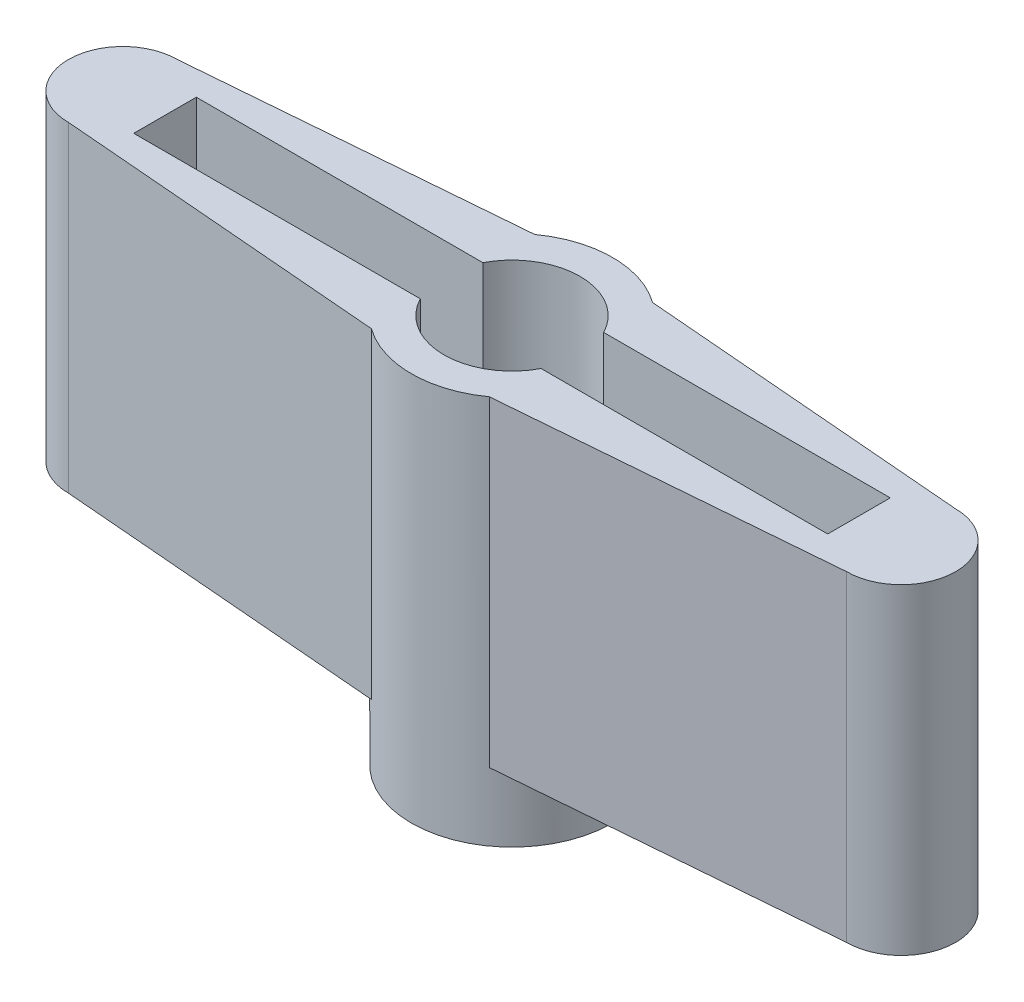
SolidWorks part; units mm, degrees
ref_plane "Alzado" through (0, 0, 0) normal (0, 0, 1) x (1, 0, 0)
ref_plane "Planta" through (0, 0, 0) normal (0, 1, 0) x (1, 0, 0)
ref_plane "Vista lateral" through (0, 0, 0) normal (1, 0, 0) x (0, 0, -1)
sketch "Croquis1" plane through (0, 0, 0) normal (0, 1, 0) x (1, 0, 0)
  circle A0 centre (0, 0) radius 3.7
  dimension "D1" = 7.4
extrude "Saliente-Extruir2" add sketch "Croquis1" along normal blind 4.3 contours A0
sketch "Croquis2" plane through (0, 0, 0) normal (0, -1, 0) x (1, 0, 0)
  circle A0 centre (0, 0) radius 2.5
  dimension "D1" = 5
extrude "Cortar-Extruir1" cut sketch "Croquis2" against normal blind 1.5
sketch "Croquis3" plane through (0, 4.3, 0) normal (0, 1, 0) x (1, 0, 0)
  circle A0 centre (0, 0) radius 2.5
  dimension "D1" = 5
extrude "Cortar-Extruir2" cut sketch "Croquis3" against normal blind 1
sketch "Croquis4" plane through (0, 3.3, 0) normal (0, 1, 0) x (1, 0, 0)
  circle A0 centre (0, 0) radius 1
  dimension "D1" = 2
extrude "Cortar-Extruir3" cut sketch "Croquis4" against normal blind 1.8
sketch "Croquis5" plane through (0, 4.3, 0) normal (0, 1, 0) x (1, 0, 0)
  line L0 (0, 0) -> (-2.1656, 0) construction
  line L1 (-2.1656, 3) -> (-3.1202, 0)
  line L2 (-3.1202, 0) -> (-2.1656, -3)
  line L3 (-2.1656, 0) -> (-2.5, 0) construction
  line L4 (-3.7, 0) -> (-16.3, 0) construction
  line L5 (-14.3, 0) -> (-14.3, 2) construction
  line L6 (-14.3, 0) -> (-14.3, -2) construction
  line L7 (-2.1656, 3) -> (-14.3, 2)
  line L8 (-2.1656, -3) -> (-14.3, -2)
  line L9 (0, 5.1944) -> (0, -4.3435) construction
  line L10 (3.1202, 0) -> (2.1656, -3)
  line L11 (2.1656, -3) -> (14.3, -2)
  line L12 (2.1656, 3) -> (14.3, 2)
  line L13 (2.1656, 3) -> (3.1202, 0)
  arc A0 (-14.3, 2) -> (-14.3, -2) centre (-14.3, 0) ccw
  arc A1 (14.3, 2) -> (14.3, -2) centre (14.3, 0) cw
  circle A3 centre (0, 0) radius 3.7 construction
  circle A4 centre (0, 0) radius 2.5 construction
  point P2 (-14.3, 0)
  dimension "D1" = 2.1656
  dimension "D2" = 12.6
  dimension "D3" = 2
  dimension "D4" = 2
  dimension "D5" = 2
extrude "Saliente-Extruir3" add sketch "Croquis5" against normal blind 1.8
sketch "Croquis6" plane through (0, 4.3, 0) normal (0, 1, 0) x (1, 0, 0)
  line L0 (0, 0) -> (-16.3, 0) construction
  line L1 (2, 0) -> (-14.3, 0) construction
  line L2 (4, 0) -> (-12.3, 0) construction
  line L3 (6, 0) -> (-10.3, 0) construction
  line L4 (8, 0) -> (-8.3, 0) construction
  line L5 (10, 0) -> (-6.3, 0) construction
  line L6 (0, 5.4913) -> (0, -4.5375) construction
  arc A0 (-14.3, 2) -> (-14.3, -2) centre (-14.3, 0) ccw construction
  circle A1 centre (-14.705, 0) radius 0.595
  circle A2 centre (-12.705, 0) radius 0.595
  circle A3 centre (-10.705, 0) radius 0.595
  circle A4 centre (-8.705, 0) radius 0.595
  circle A5 centre (-6.705, 0) radius 0.595
  circle A6 centre (-4.705, 0) radius 0.595
  circle A7 centre (14.705, 0) radius 0.595
  circle A8 centre (12.705, 0) radius 0.595
  circle A9 centre (10.705, 0) radius 0.595
  circle A10 centre (8.705, 0) radius 0.595
  circle A11 centre (6.705, 0) radius 0.595
  circle A12 centre (4.705, 0) radius 0.595
  point P6 (-14.705, 0)
  dimension "D2" = 1.19
  dimension "D1" = 1.595
  dimension "D3" = 6
extrude "Cortar-Extruir4" cut sketch "Croquis6" against normal blind 1.8
sketch "Sketch1" plane through (0, 4.3, 0) normal (0, 1, 0) x (1, 0, 0)
  line L12 (2.1656, -3) -> (14.3, -2)
  line L13 (14.3, 2) -> (2.1656, 3)
  line L14 (-2.1656, 3) -> (-14.3, 2)
  line L15 (-14.3, -2) -> (-2.1656, -3)
  line L16 (2.1656, -3) -> (14.3, -2)
  line L17 (14.3, 2) -> (2.1656, 3)
  line L18 (-2.1656, 3) -> (-14.3, 2)
  line L19 (-14.3, -2) -> (-2.1656, -3)
  circle A0 centre (0, 0) radius 2.5
  arc A13 (-2.1656, -3) -> (2.1656, -3) centre (0, 0) ccw
  arc A14 (14.3, -2) -> (14.3, 2) centre (14.3, 0) ccw
  arc A15 (2.1656, 3) -> (-2.1656, 3) centre (0, 0) ccw
  arc A16 (-14.3, 2) -> (-14.3, -2) centre (-14.3, 0) ccw
  arc A17 (-2.1656, -3) -> (2.1656, -3) centre (0, 0) ccw
  arc A18 (14.3, -2) -> (14.3, 2) centre (14.3, 0) ccw
  arc A19 (2.1656, 3) -> (-2.1656, 3) centre (0, 0) ccw
  arc A20 (-14.3, 2) -> (-14.3, -2) centre (-14.3, 0) ccw
  dimension "D1" = 0
extrude "Boss-Extrude1" add sketch "Sketch1" along normal blind 10
sketch "Sketch2" plane through (0, 14.3, 0) normal (0, 1, 0) x (1, 0, 0)
  line L1 (-12.75, -1.15) -> (12.75, -1.15)
  line L2 (-12.75, -1.15) -> (-12.75, 1.15)
  line L3 (-12.75, 1.15) -> (12.75, 1.15)
  line L4 (12.75, -1.15) -> (12.75, 1.15)
  line L5 (-12.75, -1.15) -> (12.75, 1.15) construction
  line L6 (-12.75, 1.15) -> (12.75, -1.15) construction
  point P0 (0, 0)
  dimension "D1" = 2.3
  dimension "D2" = 25.5
extrude "Cut-Extrude1" cut sketch "Sketch2" against normal blind 7
